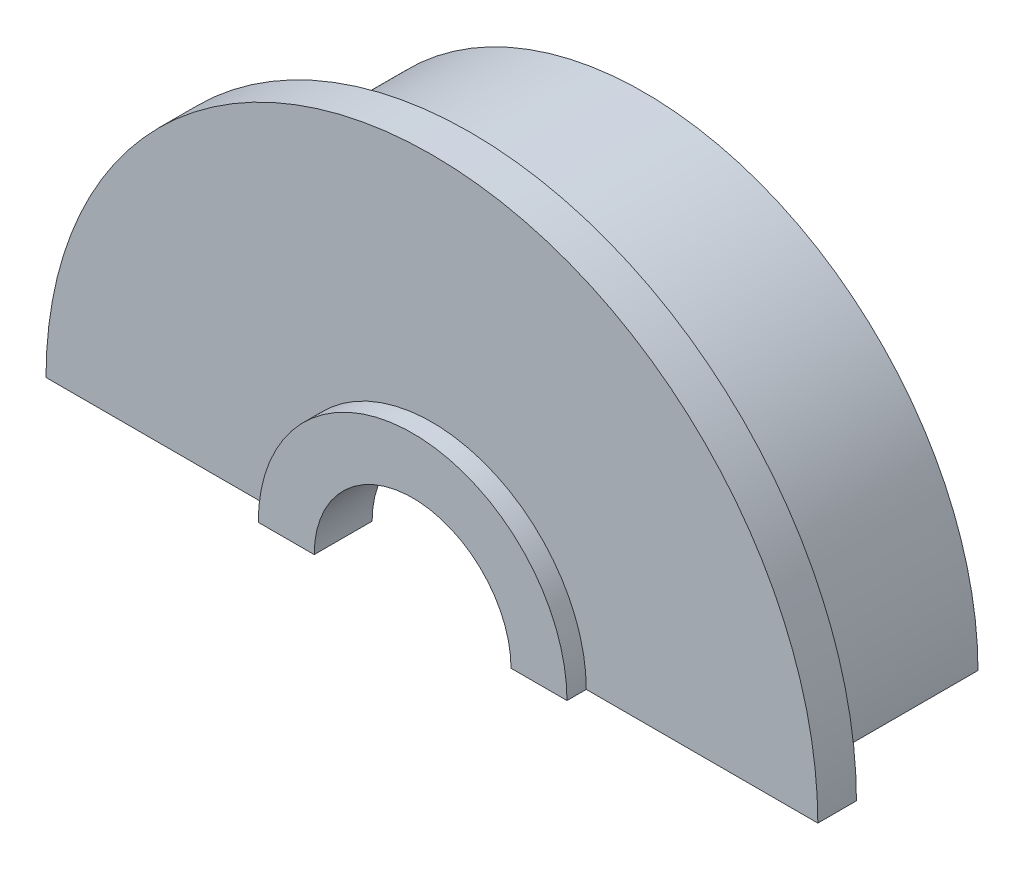
SolidWorks part; units mm, degrees
ref_plane "Front" through (0, 0, 0) normal (0, 0, 1) x (1, 0, 0)
ref_plane "Top" through (0, 0, 0) normal (0, 1, 0) x (1, 0, 0)
ref_plane "Right" through (0, 0, 0) normal (1, 0, 0) x (0, 0, -1)
sketch "Sketch1" plane through (0, 0, 0) normal (0, 0, 1) x (1, 0, 0)
  circle A1 centre (0, 0) radius 17.3
extrude "Boss-Extrude1" add sketch "Sketch1" along normal blind 9
sketch "Sketch2" plane through (0, 0, 9) normal (0, 0, 1) x (1, 0, 0)
  circle A0 centre (0, 0) radius 5.1
  point P0 (0, 0)
extrude "Cut-Extrude1" cut sketch "Sketch2" against normal blind 10
sketch "Sketch3" plane through (0, 0, 0) normal (0, 0, -1) x (-1, 0, 0)
  circle A0 centre (0, 0) radius 8.125
extrude "Cut-Extrude2" cut sketch "Sketch3" against normal blind 9
sketch "Sketch4" plane through (0, 0, 9) normal (0, 0, 1) x (1, 0, 0)
  circle A0 centre (0, 0) radius 20
  circle A1 centre (0, 0) radius 5.1
extrude "Boss-Extrude2" add sketch "Sketch4" along normal blind 2
sketch "Sketch5" plane through (0, 0, 0) normal (0, 0, -1) x (-1, 0, 0)
  line L0 (-25.5515, 0) -> (26.4698, 0)
  line L1 (26.4698, 0) -> (26.4698, -22.6614)
  line L2 (26.4698, -22.6614) -> (-25.5515, -22.6614)
  line L3 (-25.5515, -22.6614) -> (-25.5515, 0)
extrude "Cut-Extrude3" cut sketch "Sketch5" against normal through all both and the other way through all
sketch "Sketch7" plane through (0, 0, 11) normal (0, 0, 1) x (1, 0, 0)
  line L0 (-5.1, 0) -> (-8, 0)
  line L1 (5.1, 0) -> (8, 0)
  circle A0 centre (0, 0) radius 5.1 construction
  circle A1 centre (0, 0) radius 8 construction
  arc A2 (-8, 0) -> (8, 0) centre (0, 0) cw
  arc A3 (5.1, 0) -> (-5.1, 0) centre (0, 0) ccw
extrude "Boss-Extrude3" add sketch "Sketch7" along normal blind 1
sketch "Sketch8" plane through (0, 0, 0) normal (0, 0, -1) x (-1, 0, 0)
  circle A0 centre (0, 0) radius 10.75
extrude "Cut-Extrude4" cut sketch "Sketch8" against normal blind 3
